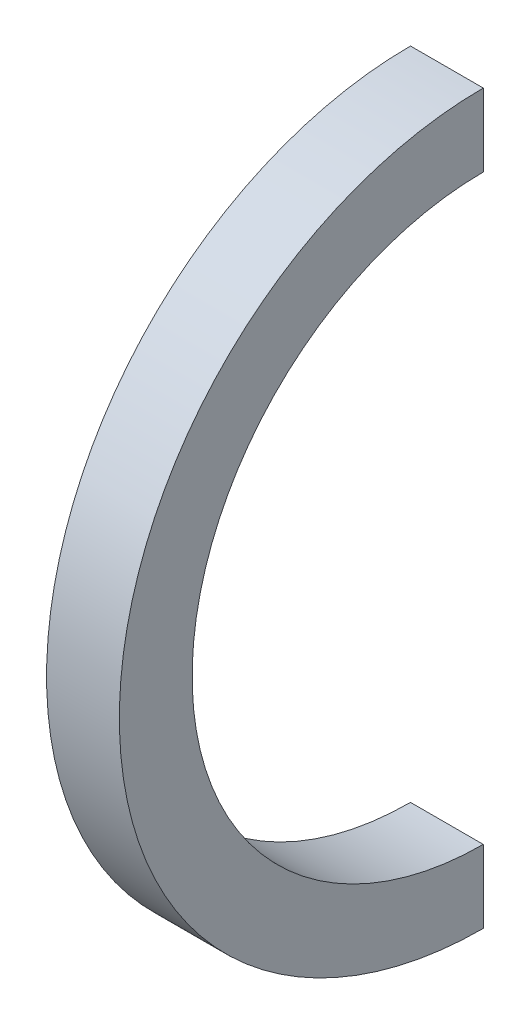
SolidWorks part; units mm, degrees
ref_plane "Front Plane" through (0, 0, 0) normal (0, 0, 1) x (1, 0, 0)
ref_plane "Top Plane" through (0, 0, 0) normal (0, 1, 0) x (1, 0, 0)
ref_plane "Right Plane" through (0, 0, 0) normal (1, 0, 0) x (0, 0, -1)
sketch "Sketch1" plane through (0, 0, 0) normal (0, 0, 1) x (1, 0, 0)
  line L1 (0, 0) -> (-25.4, 0)
  line L2 (0, 0) -> (0, 25.4)
  line L3 (0, 25.4) -> (-25.4, 25.4)
  line L4 (-25.4, 0) -> (-25.4, 25.4)
  line L5 (-19.05, 19.05) -> (-6.35, 19.05)
  line L6 (-19.05, 19.05) -> (-19.05, 6.35)
  line L7 (-19.05, 6.35) -> (-6.35, 6.35)
  line L8 (-6.35, 19.05) -> (-6.35, 6.35)
  dimension "D1" = 25.4
  dimension "D2" = 25.4
  dimension "D3" = 6.35
  dimension "D4" = 6.35
  dimension "D5" = 6.35
  dimension "D6" = 6.35
sketch "Sketch2" plane through (0, 0, 0) normal (0, 0, 1) x (1, 0, 0)
  line L0 (0, 127) -> (-25.4, 127)
  line L1 (0, 25.4) -> (-25.4, 25.4) construction
  dimension "D1" = 25.4
  dimension "D2" = 101.6
revolve "Revolve2" add sketch "Sketch1" angle 180 about L0
